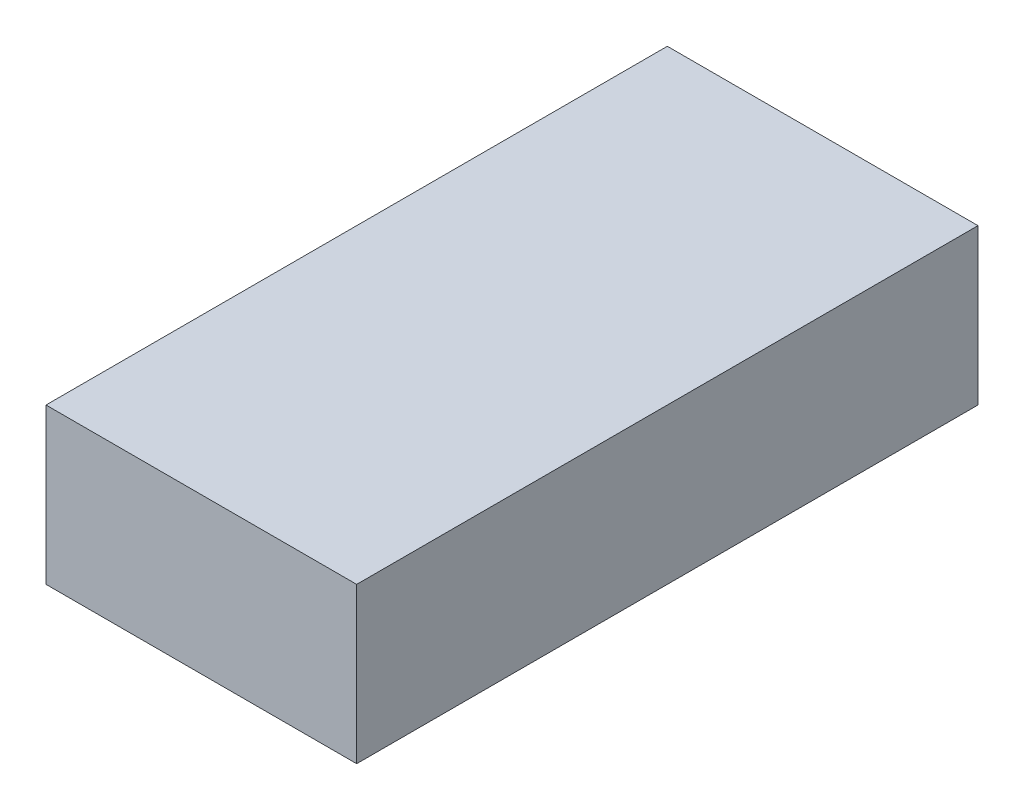
SolidWorks part; units mm, degrees
ref_plane "Front Plane" through (0, 0, 0) normal (0, 0, 1) x (1, 0, 0)
ref_plane "Top Plane" through (0, 0, 0) normal (0, 1, 0) x (1, 0, 0)
ref_plane "Right Plane" through (0, 0, 0) normal (1, 0, 0) x (0, 0, -1)
sketch "Sketch1" plane through (0, 0, 0) normal (0, 0, 1) x (1, 0, 0)
  line L1 (0, 0) -> (-12.7, 0)
  line L2 (0, 0) -> (0, 6.35)
  line L3 (0, 6.35) -> (-12.7, 6.35)
  line L4 (-12.7, 0) -> (-12.7, 6.35)
  dimension "D1" = 12.7
  dimension "D2" = 6.35
extrude "Boss-Extrude1" add sketch "Sketch1" along normal blind 25.4
